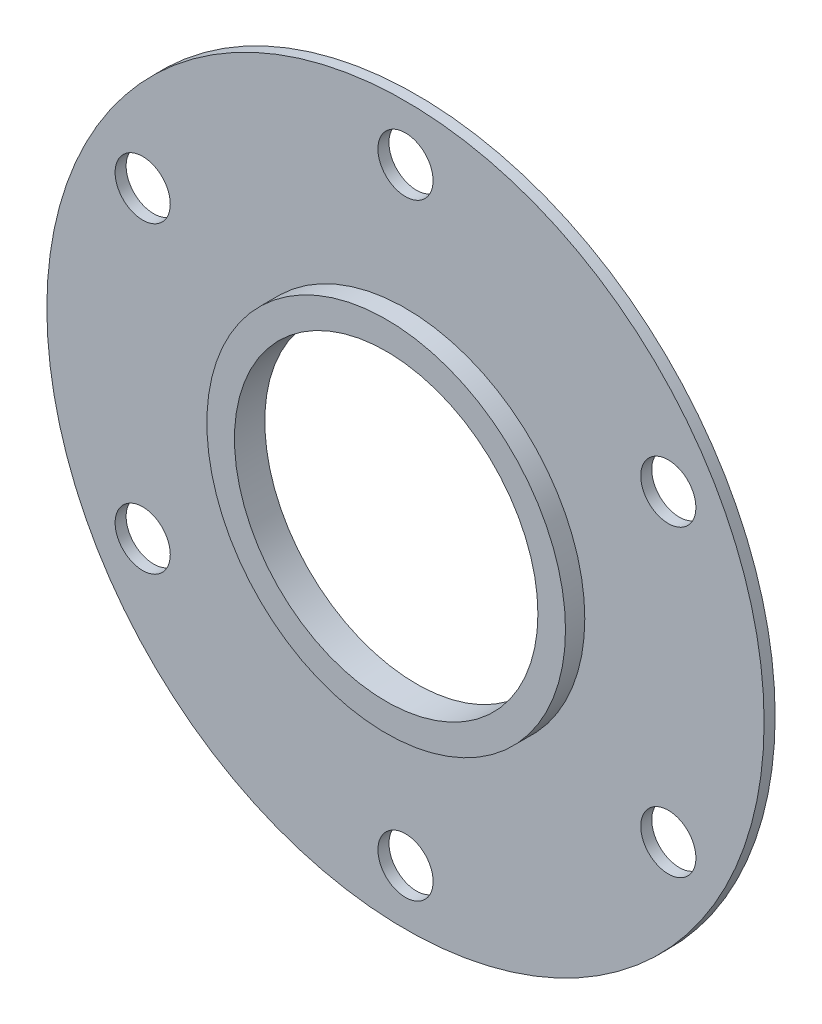
SolidWorks part; units mm, degrees
ref_plane "Plan de face" through (0, 0, 0) normal (0, 0, 1) x (1, 0, 0)
ref_plane "Plan de dessus" through (0, 0, 0) normal (0, 1, 0) x (1, 0, 0)
ref_plane "Plan de droite" through (0, 0, 0) normal (1, 0, 0) x (0, 0, -1)
sketch "Esquisse1" plane through (0, 0, 0) normal (0, 0, 1) x (1, 0, 0)
  circle A1 centre (0, 22) radius 2
  circle A2 centre (0, 0) radius 26
  circle A3 centre (19.0531, 11.0009) radius 2
  circle A4 centre (19.0541, -10.9991) radius 2
  circle A5 centre (0.002, -22) radius 2
  circle A6 centre (-19.0511, -11.0009) radius 2
  circle A7 centre (-19.0521, 10.9991) radius 2
  circle A8 centre (0, 0) radius 11
  point P18 (0.001, 0)
  dimension "D2" = 22
  dimension "D1" = 6
extrude "Boss.-Extru.1" add sketch "Esquisse1" along normal blind 0.8
sketch "Esquisse2" plane through (0, 0, 0.8) normal (0, 0, 1) x (1, 0, 0)
  circle A0 centre (0, 0) radius 11
  circle A1 centre (0, 0) radius 13
  dimension "D1" = 26
extrude "Boss.-Extru.2" add sketch "Esquisse2" along normal blind 1.4
